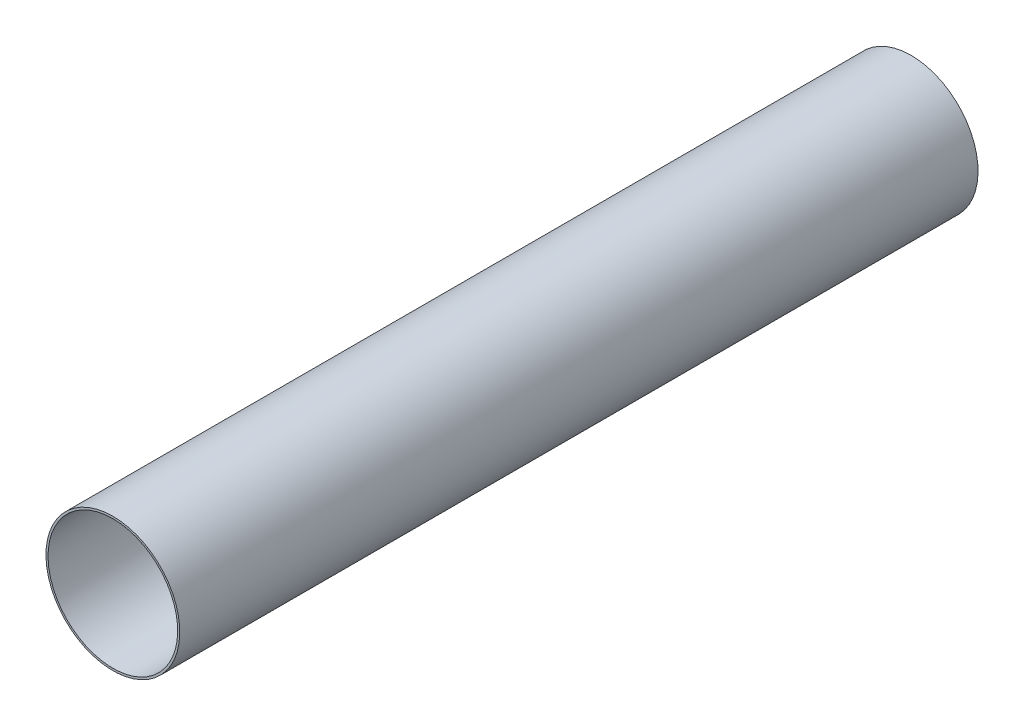
SolidWorks part; units mm, degrees
ref_plane "Plan de face" through (0, 0, 0) normal (0, 0, 1) x (1, 0, 0)
ref_plane "Plan de dessus" through (0, 0, 0) normal (0, 1, 0) x (1, 0, 0)
ref_plane "Plan de droite" through (0, 0, 0) normal (1, 0, 0) x (0, 0, -1)
sketch "Esquisse2" plane through (0, 0, 0) normal (1, 0, 0) x (0, 0, -1)
  line L0 (-10, 51.11) -> (-10, 49.53)
  line L2 (-10, 49.53) -> (-620, 49.53)
  line L19 (-620, 49.53) -> (-620, 51.11)
  line L20 (-620, 51.11) -> (-10, 51.11)
  line L24 (0, 0) -> (-694.9162, 0) construction
  dimension "D2" = 610
  dimension "D3" = 1.58
  dimension "D1" = 10
  dimension "D4" = 99.06
revolve "Révolution1" add sketch "Esquisse2" angle 360 about L24
equation "\"D4@Esquisse2\"=\"d_i_motor_tube\""
equation "\"D3@Esquisse2\"=\"t_motor_tube\""
equation "\"D2@Esquisse2\"=\"l_motor_tube\""
equation "\"d_i_tube\"= 150mm'Inner Rocket Body Composite Tube Diameter"
equation "\"t_tube\"= 1.182mm'Thickness of Rocket Body Composite Tube"
equation "\"l_upper_body_tube\"= 949.3mm'Upper Rocket Body Composite Tube length"
equation "\"l_lower_body_tube\"= 816mm'Lower Rocket Body Composite Tube Length"
equation "\"d_a_NC\"= 154mm'Outer Diameter of Nosecone base"
equation "\"d_i_phenolic_tube\"= 152.3mm'Inner Phenolic Tube Diameter"
equation "\"t_phenolic_tube\"= 2mm'Thickness of Phenolic Body Tube"
equation "\"l_fin_cut\"= 220mm'Length of fin on Motor Retainer"
equation "\"t_SW-Panel\"= 11.482mm'Thickness of Sandwich-Panel"
equation "\"l_motor_tube\"=610mm'Length of phenolic motor tube"
equation "\"d_i_motor_tube\"=99.06mm'Inner diameter of phenolic motor tube"
equation "\"t_motor_tube\"=1.58mm'Thicknes of phenolic motor tube"
equation "\"l_cut_fin_centering\"=13mm'Length of cut for fin alignement on fin centering rings"
equation "\"l_M3_threaded_rods\"=220mm'Length of M3 threaded rods for thrust plate force transmission"
